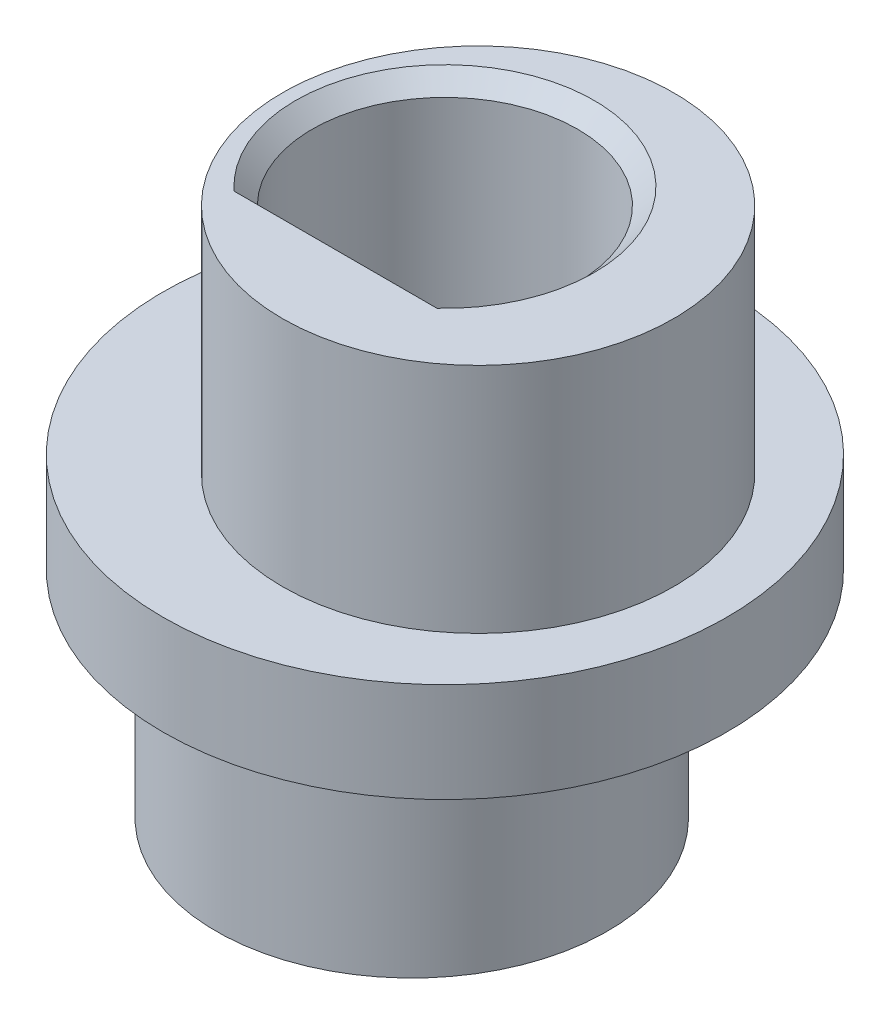
SolidWorks part; units mm, degrees
ref_plane "Ebene vorne" through (0, 0, 0) normal (0, 0, 1) x (1, 0, 0)
ref_plane "Ebene oben" through (0, 0, 0) normal (0, 1, 0) x (1, 0, 0)
ref_plane "Ebene rechts" through (0, 0, 0) normal (1, 0, 0) x (0, 0, -1)
sketch "Skizze1" plane through (0, 0, 0) normal (0, 1, 0) x (1, 0, 0)
  circle A0 centre (0, 0) radius 8.5
  dimension "D1" = 17
extrude "Aufsatz-Linear austragen1" add sketch "Skizze1" along normal mid plane 3
sketch "Skizze2" plane through (0, 1.5, 0) normal (0, 1, 0) x (1, 0, 0)
  line L0 (0, 0) -> (-50000, 0) construction
  circle A0 centre (1, 0) radius 5.9
  dimension "D2" = 11.8
  dimension "D1" = 1
extrude "Aufsatz-Linear austragen2" add sketch "Skizze2" along normal blind 7
sketch "Skizze3" plane through (0, -1.5, 0) normal (0, -1, 0) x (1, 0, 0)
  line L0 (0, 0) -> (-50000, 0) construction
  circle A0 centre (-1, 0) radius 5.9
  dimension "D2" = 11.8
  dimension "D1" = 1
extrude "Aufsatz-Linear austragen3" add sketch "Skizze3" along normal blind 7
sketch "Skizze4" plane through (0, 8.5, 0) normal (0, 1, 0) x (1, 0, 0)
  line L0 (-2.8566, -2.8) -> (2.8566, -2.8)
  arc A0 (2.8566, -2.8) -> (-2.8566, -2.8) centre (0, 0) ccw
  dimension "D1" = 8
  dimension "D2" = 6.8
extrude "Schnitt-Linear austragen1" cut sketch "Skizze4" against normal through all
chamfer "Fase1" distance 0.5 angle 45 4 edges at (0, -8.5, 2.8) (0, -8.5, -4) (0, 8.5, 2.8) (0, 8.5, -4)
